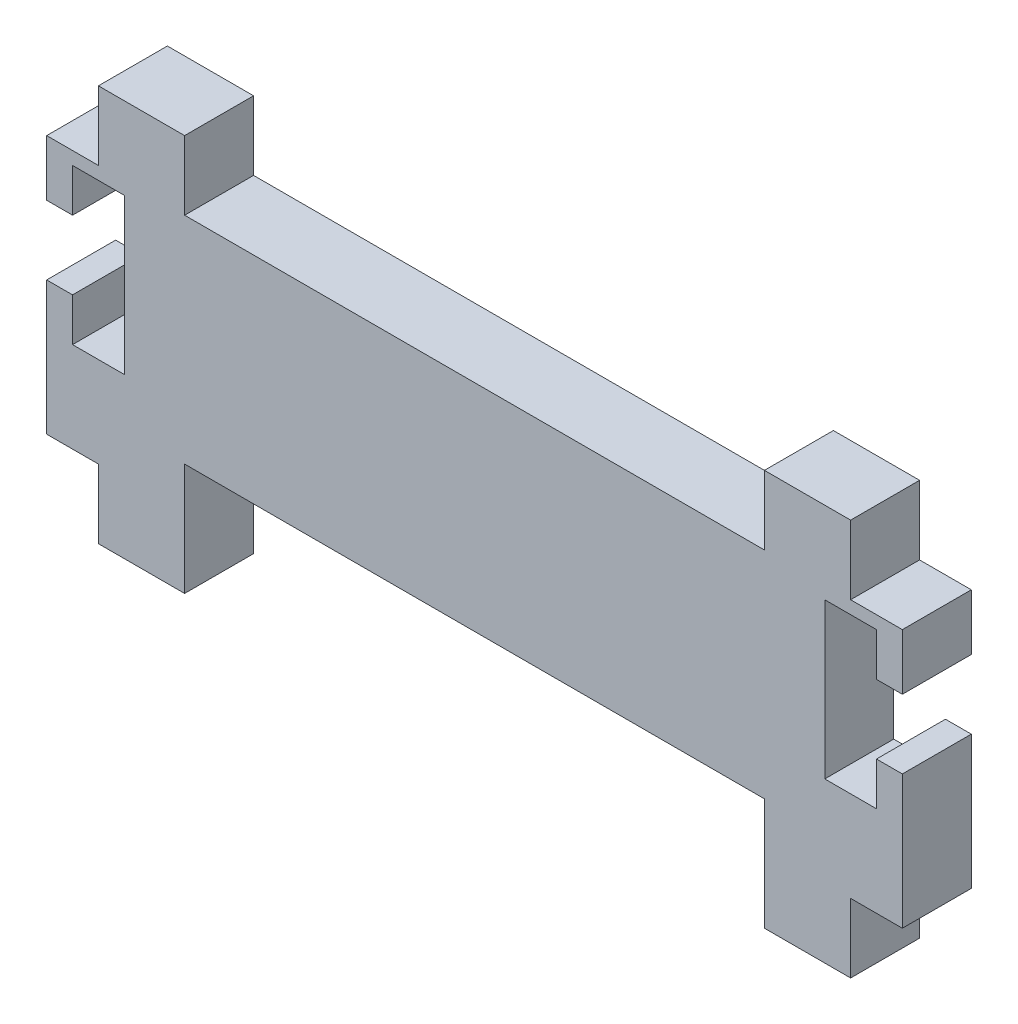
SolidWorks part; units mm, degrees
ref_plane "Alzado" through (0, 0, 0) normal (0, 0, 1) x (1, 0, 0)
ref_plane "Planta" through (0, 0, 0) normal (0, 1, 0) x (1, 0, 0)
ref_plane "Vista lateral" through (0, 0, 0) normal (1, 0, 0) x (0, 0, -1)
sketch "Croquis1" plane through (0, 0, 0) normal (0, 0, 1) x (1, 0, 0)
  line L0 (-12.0787, -9.5641) -> (-13.5787, -9.5641)
  line L1 (-10.5787, -17.3141) -> (-10.5787, -21.3141)
  line L2 (-10.5787, -21.3141) -> (-5.5787, -21.3141)
  line L3 (-5.5787, -21.3141) -> (-5.5787, -17.3141)
  line L4 (-5.5787, -17.3141) -> (-5.5787, -14.8141)
  line L5 (28.0513, -14.8141) -> (-5.5787, -14.8141)
  line L6 (33.0513, -2.3141) -> (33.0513, 1.6859)
  line L7 (36.0513, -2.3141) -> (33.0513, -2.3141)
  line L8 (28.0513, 1.6859) -> (28.0513, -2.3141)
  line L9 (33.0513, 1.6859) -> (28.0513, 1.6859)
  line L10 (-13.5787, -17.3141) -> (-10.5787, -17.3141)
  line L11 (-10.5787, 1.6859) -> (-5.5787, 1.6859)
  line L12 (-5.5787, 1.6859) -> (-5.5787, -2.3141)
  line L13 (36.0513, -17.3141) -> (33.0513, -17.3141)
  line L14 (28.0513, -17.3141) -> (28.0513, -14.8141)
  line L15 (28.0513, -21.3141) -> (28.0513, -17.3141)
  line L16 (-13.5787, -2.3141) -> (-10.5787, -2.3141)
  line L17 (-10.5787, -2.3141) -> (-10.5787, 1.6859)
  line L18 (-13.5787, -2.3141) -> (-13.5787, -5.5641)
  line L19 (28.0513, -2.3141) -> (-5.5787, -2.3141)
  line L20 (33.0513, -21.3141) -> (28.0513, -21.3141)
  line L21 (33.0513, -17.3141) -> (33.0513, -21.3141)
  line L22 (-9.0787, -3.0641) -> (-9.0787, -12.0641)
  line L23 (31.5513, -3.0641) -> (31.5513, -12.0641)
  line L24 (-9.0787, -3.0641) -> (-12.0787, -3.0641)
  line L25 (-12.0787, -3.0641) -> (-12.0787, -5.5641)
  line L26 (-12.0787, -5.5641) -> (-13.5787, -5.5641)
  line L27 (-12.0787, -12.0641) -> (-12.0787, -9.5641)
  line L28 (-9.0787, -12.0641) -> (-12.0787, -12.0641)
  line L29 (36.0513, -17.3141) -> (36.0513, -9.5641)
  line L30 (31.5513, -12.0641) -> (34.5513, -12.0641)
  line L31 (34.5513, -12.0641) -> (34.5513, -9.5641)
  line L32 (34.5513, -5.5641) -> (36.0513, -5.5641)
  line L33 (34.5513, -3.0641) -> (34.5513, -5.5641)
  line L34 (31.5513, -3.0641) -> (34.5513, -3.0641)
  line L36 (36.0513, -2.3141) -> (36.0513, -5.5641)
  line L37 (-13.5787, -17.3141) -> (-13.5787, -9.5641)
  line L38 (34.5513, -9.5641) -> (36.0513, -9.5641)
extrude "Saliente-Extruir1" add sketch "Croquis1" along normal blind 4
